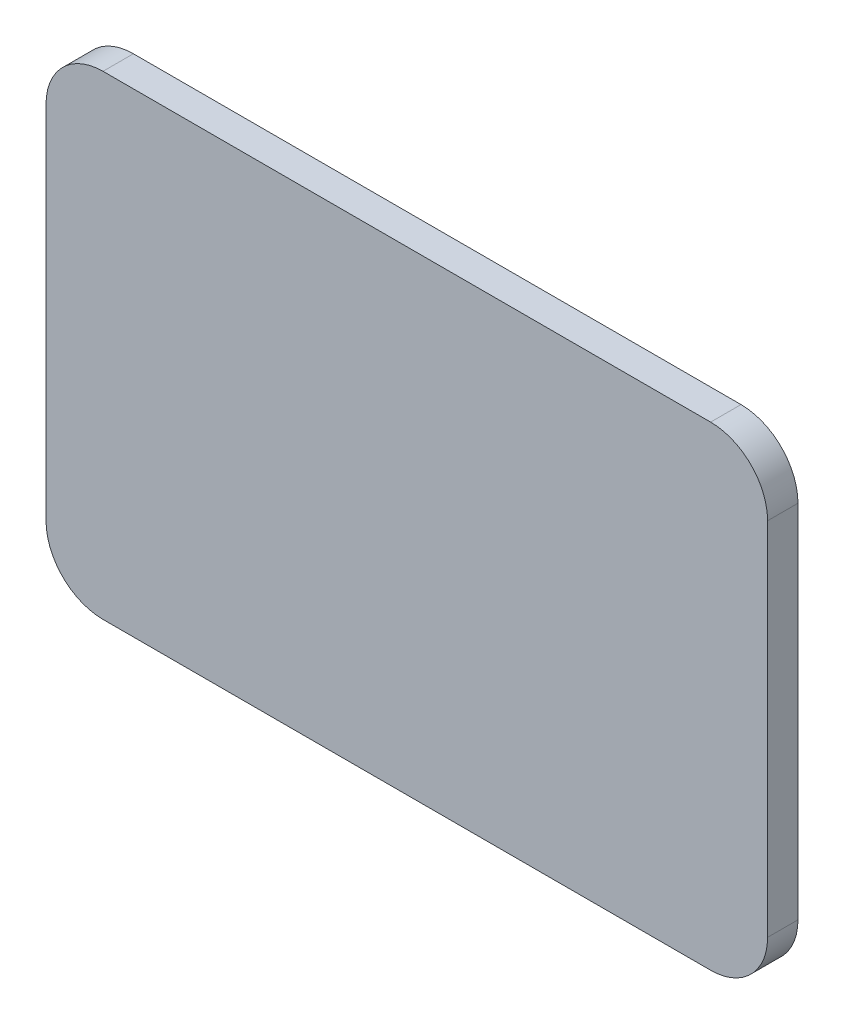
SolidWorks part; units mm, degrees
material "Q235A"
ref_plane "前视" through (0, 0, 0) normal (0, 0, 1) x (1, 0, 0)
ref_plane "上视" through (0, 0, 0) normal (0, 1, 0) x (1, 0, 0)
ref_plane "右视" through (0, 0, 0) normal (1, 0, 0) x (0, 0, -1)
sketch "草图1" plane through (0, 0, 0) normal (0, 0, 1) x (1, 0, 0)
  line L1 (190, -125) -> (-190, -125)
  line L2 (190, -125) -> (190, 125)
  line L3 (190, 125) -> (-190, 125)
  line L4 (-190, -125) -> (-190, 125)
  line L5 (190, -125) -> (-190, 125) construction
  line L6 (190, 125) -> (-190, -125) construction
  point P0 (0, 0)
  dimension "D1" = 250
  dimension "D2" = 380
extrude "凸台-拉伸1" add sketch "草图1" along normal blind 16
fillet "圆角1" radius 30 4 edges at (190, -125, 8) (190, 125, 8) (-190, -125, 8) (-190, 125, 8)
